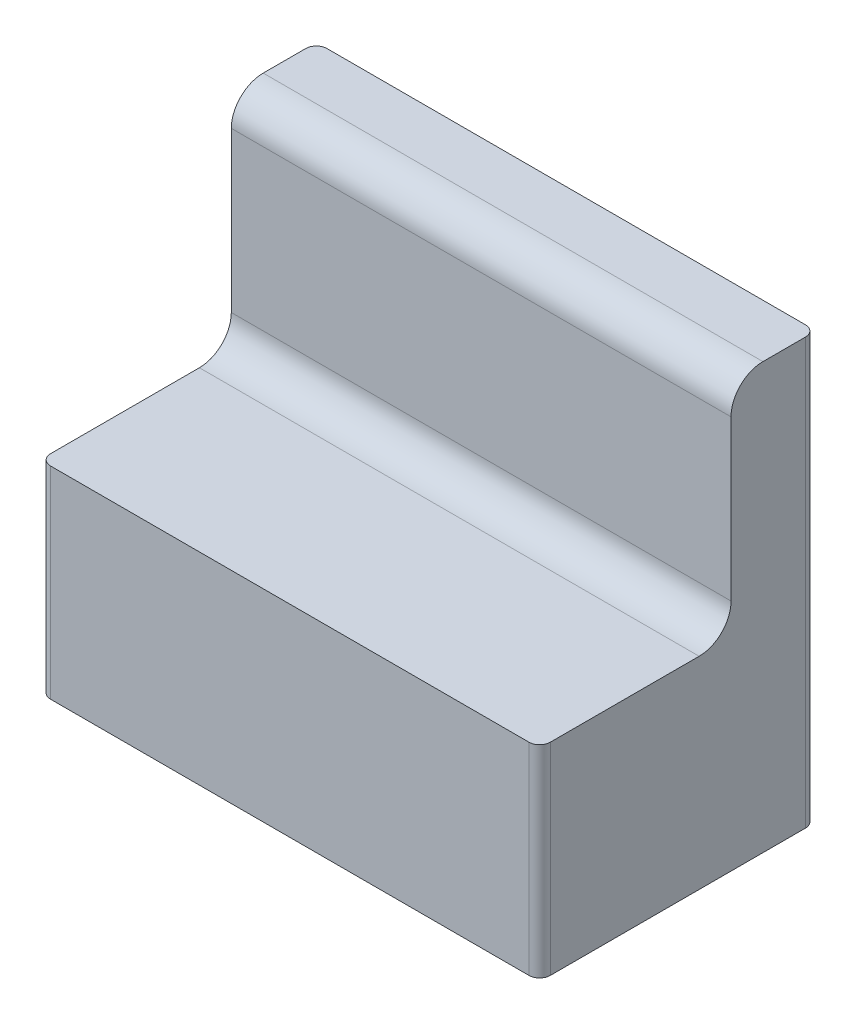
SolidWorks part; units mm, degrees
material "K110"
ref_plane "Front Plane" through (0, 0, 0) normal (0, 0, 1) x (1, 0, 0)
ref_plane "Top Plane" through (0, 0, 0) normal (0, 1, 0) x (1, 0, 0)
ref_plane "Right Plane" through (0, 0, 0) normal (1, 0, 0) x (0, 0, -1)
sketch "Sketch1" plane through (0, 0, 0) normal (0, 1, 0) x (1, 0, 0)
  line L1 (-23.5, -13) -> (23.5, -13)
  line L2 (-23.5, -13) -> (-23.5, 13)
  line L3 (-23.5, 13) -> (23.5, 13)
  line L4 (23.5, -13) -> (23.5, 13)
  line L5 (-23.5, -13) -> (23.5, 13) construction
  line L6 (-23.5, 13) -> (23.5, -13) construction
  point P0 (0, 0)
  dimension "D1" = 26
  dimension "D2" = 47
extrude "Boss-Extrude1" add sketch "Sketch1" against normal blind 40
sketch "Sketch2" plane through (23.5, 0, 0) normal (1, 0, 0) x (0, 0, -1)
  line L0 (13, -40) -> (13, 0) construction
  line L1 (-13, 0) -> (5, 0)
  line L2 (-13, 0) -> (-13, -21)
  line L3 (-13, -21) -> (5, -21)
  line L4 (5, 0) -> (5, -21)
  dimension "D1" = 8
  dimension "D2" = 21
extrude "Cut-Extrude1" cut sketch "Sketch2" against normal up to next
fillet "Fillet1" radius 3 2 edges at (0, 0, -5) (0, -21, -5)
hole_wizard "M6 Tapped Hole1" positions "Sketch6" profile "Sketch4" tap size "M6" standard "ISO"
sketch "Sketch6" plane through (0, -40, 0) normal (0, -1, 0) x (-1, 0, 0)
  line L0 (-23.5, -13) -> (-23.5, 13) construction
  line L1 (23.5, 13) -> (23.5, -13) construction
  point P0 (-15.5, 0)
  point P2 (15.5, 0)
  dimension "D1" = 8
  dimension "D2" = 8
sketch "Sketch4" plane through (15.5, -40, 0) normal (1, 0, 0) x (0, 0, -1)
  line L0 (0, 0) -> (0, 16.5022)
  line L1 (0, 16.5022) -> (2.5, 15)
  line L2 (2.5, 15) -> (2.5, 0.525)
  line L3 (2.5, 0.525) -> (3.025, 0)
  line L5 (3.025, 0) -> (0, 0)
  line L6 (-2.5, 0.525) -> (-3.025, 0) construction
  line L10 (0, 16.5022) -> (-2.5, 15) construction
  line L11 (0, -6.35) -> (0, 107.95) construction
  dimension "Tap Drill Dia." = 5
  dimension "Tap Drill Depth" = 15
  dimension "Near C'Sink Dia." = 6.05
  dimension "Near C'Sink Angle" = 90
  dimension "Drill Angle" = 118
cosmetic thread "Hole Thread1"
cosmetic thread "Hole Thread2"
fillet "Fillet2" radius 1 4 edges at (23.5, -20, -13) (23.5, -30.5, 13) (-23.5, -30.5, 13) (-23.5, -20, -13)
